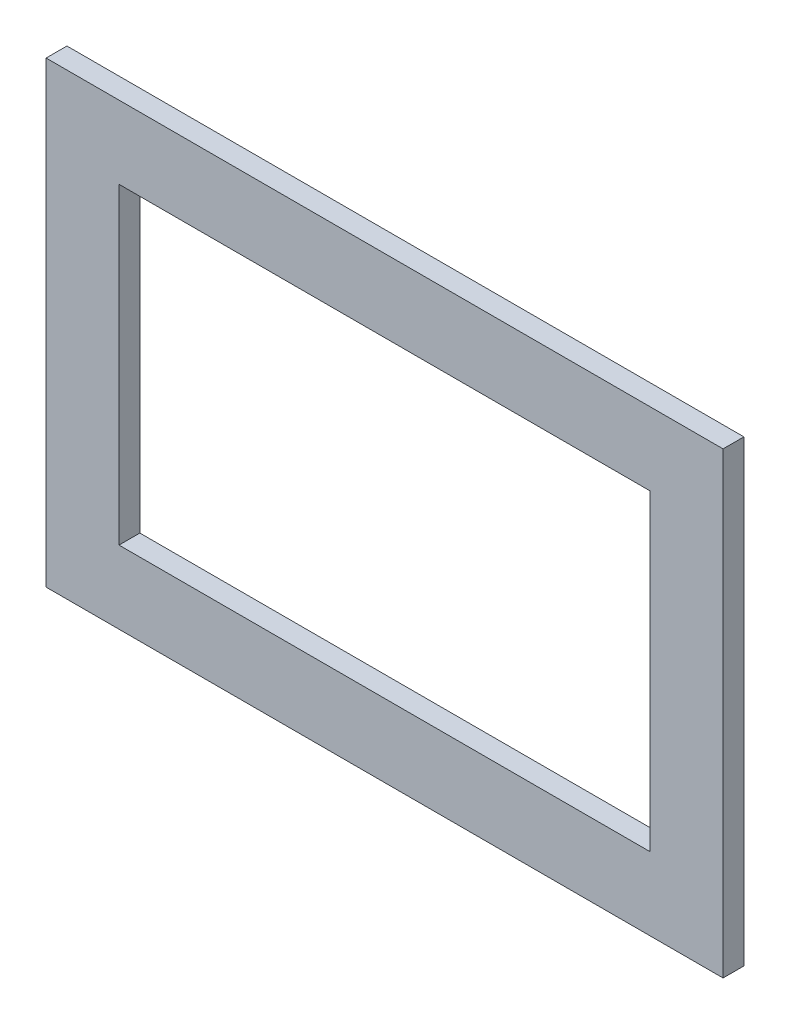
SolidWorks part; units mm, degrees
ref_plane "Front Plane" through (0, 0, 0) normal (0, 0, 1) x (1, 0, 0)
ref_plane "Top Plane" through (0, 0, 0) normal (0, 1, 0) x (1, 0, 0)
ref_plane "Right Plane" through (0, 0, 0) normal (1, 0, 0) x (0, 0, -1)
sketch "Sketch1" plane through (0, 0, 0) normal (0, 0, 1) x (1, 0, 0)
  line L1 (-266.6985, 134.0802) -> (383.3015, 134.0802)
  line L2 (-266.6985, 134.0802) -> (-266.6985, -305.9198)
  line L3 (-266.6985, -305.9198) -> (383.3015, -305.9198)
  line L4 (383.3015, 134.0802) -> (383.3015, -305.9198)
  line L5 (-196.6985, 64.0802) -> (313.3015, 64.0802)
  line L6 (-196.6985, 64.0802) -> (-196.6985, -235.9198)
  line L7 (-196.6985, -235.9198) -> (313.3015, -235.9198)
  line L8 (313.3015, 64.0802) -> (313.3015, -235.9198)
  dimension "D1" = 650
  dimension "D2" = 510
  dimension "D3" = 440
  dimension "D4" = 300
  dimension "D5" = 70
  dimension "D6" = 70
extrude "Boss-Extrude1" add sketch "Sketch1" along normal blind 20
